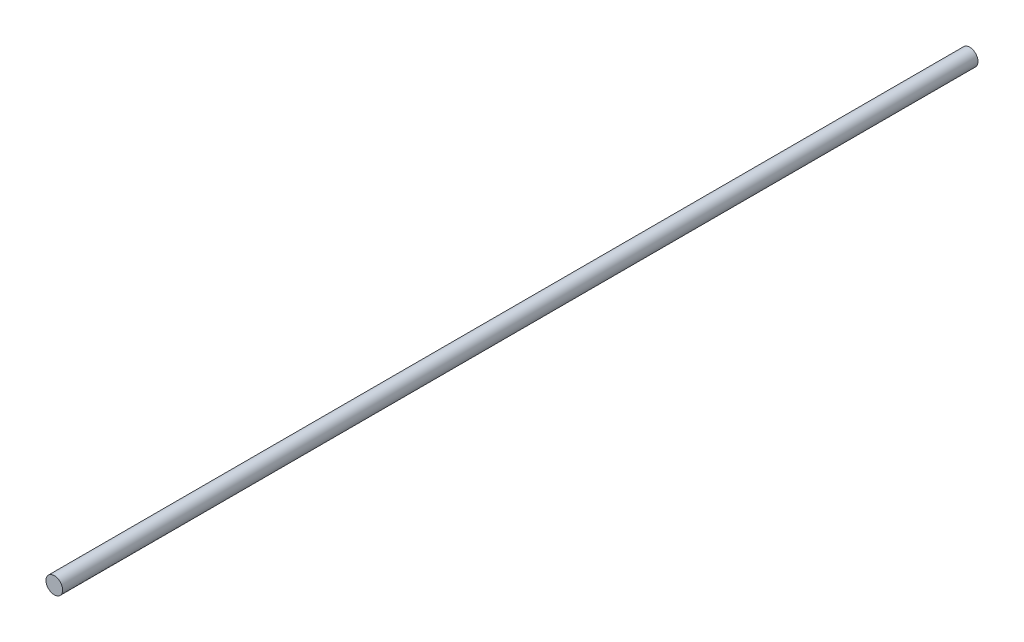
SolidWorks part; units mm, degrees
ref_plane "Front Plane" through (0, 0, 0) normal (0, 0, 1) x (1, 0, 0)
ref_plane "Top Plane" through (0, 0, 0) normal (0, 1, 0) x (1, 0, 0)
ref_plane "Right Plane" through (0, 0, 0) normal (1, 0, 0) x (0, 0, -1)
sketch "Sketch1" plane through (0, 0, 0) normal (0, 0, 1) x (1, 0, 0)
  circle A0 centre (0, 0) radius 5
  dimension "D1" = 10
extrude "Boss-Extrude2" add sketch "Sketch1" along normal blind 550
